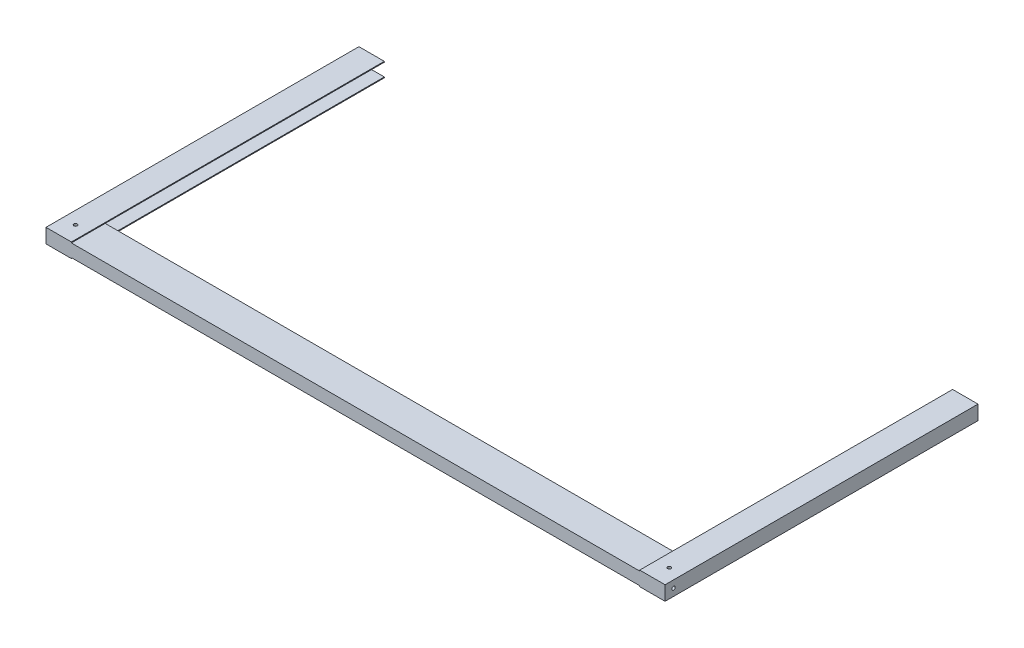
SolidWorks part; units mm, degrees
ref_plane "Alzado" through (0, 0, 0) normal (0, 0, 1) x (1, 0, 0)
ref_plane "Planta" through (0, 0, 0) normal (0, 1, 0) x (1, 0, 0)
ref_plane "Vista lateral" through (0, 0, 0) normal (1, 0, 0) x (0, 0, -1)
sketch "Croquis1" plane through (0, 0, 0) normal (0, 0, 1) x (1, 0, 0)
  line L1 (-365, -7.5) -> (365, -7.5)
  line L2 (-365, -7.5) -> (-365, 7.5)
  line L3 (-365, 7.5) -> (365, 7.5)
  line L4 (365, -7.5) -> (365, 7.5)
  line L5 (-365, -7.5) -> (365, 7.5) construction
  line L6 (-365, 7.5) -> (365, -7.5) construction
  point P0 (0, 0)
extrude "Saliente-Extruir1" add sketch "Croquis1" along normal blind 40
sketch "Croquis2" plane through (0, 0, 40) normal (0, 0, 1) x (1, 0, 0)
  line L0 (365, 7.5) -> (-365, 7.5) construction
  line L1 (-366, -8.5) -> (-336, -8.5)
  line L2 (-366, -8.5) -> (-366, 8.5)
  line L3 (-366, 8.5) -> (-336, 8.5)
  line L4 (-336, 8.5) -> (-336, 7.5)
  line L5 (-336, 7.5) -> (-365, 7.5)
  line L6 (-365, 7.5) -> (-365, -7.5)
  line L7 (-365, -7.5) -> (365, -7.5) construction
  line L8 (-365, 7.5) -> (-365, -7.5) construction
  line L9 (-365, -7.5) -> (-336, -7.5)
  line L10 (-336, -7.5) -> (-336, -8.5)
  line L11 (365, -7.5) -> (365, 7.5) construction
  line L12 (336, 8.5) -> (366, 8.5)
  line L13 (336, -8.5) -> (336, -7.5)
  line L14 (336, -8.5) -> (366, -8.5)
  line L15 (366, 8.5) -> (366, -8.5)
  line L16 (336, -7.5) -> (365, -7.5)
  line L17 (365, -7.5) -> (365, 7.5)
  line L18 (365, 7.5) -> (336, 7.5)
  line L19 (336, 7.5) -> (336, 8.5)
  dimension "D1" = 1
  dimension "D2" = 1
  dimension "D3" = 1
  dimension "D4" = 1
  dimension "D5" = 1
  dimension "D6" = 1
extrude "Saliente-Extruir2" add sketch "Croquis2" against normal blind 370
sketch "Croquis3" plane through (0, 8.5, 0) normal (0, 1, 0) x (1, 0, 0)
  line L0 (-336, -40) -> (-366, -40) construction
  line L1 (-366, 330) -> (-366, -40) construction
  line L2 (366, 330) -> (366, -40) construction
  line L3 (366, -40) -> (336, -40) construction
  circle A0 centre (351, -20) radius 2
  circle A1 centre (-351, -20) radius 2
  dimension "D1" = 20
  dimension "D2" = 15
  dimension "D3" = 15
  dimension "D4" = 20
extrude "Cortar-Extruir1" cut sketch "Croquis3" against normal blind 10
sketch "Croquis4" plane through (366, 0, 0) normal (1, 0, 0) x (0, 0, -1)
  line L0 (-40, -8.5) -> (-40, 8.5) construction
  line L1 (330, 8.5) -> (-40, 8.5) construction
  circle A0 centre (-30, 0) radius 2
  dimension "D1" = 10
  dimension "D2" = 8.5
extrude "Cortar-Extruir2" cut sketch "Croquis4" against normal blind 10
sketch "Croquis5" plane through (-366, 0, 0) normal (-1, 0, 0) x (0, 0, 1)
  line L0 (40, 8.5) -> (40, -8.5) construction
  line L1 (-330, 8.5) -> (40, 8.5) construction
  circle A0 centre (30, 0) radius 2
  dimension "D1" = 10
  dimension "D2" = 8.5
extrude "Cortar-Extruir3" cut sketch "Croquis5" against normal blind 10
